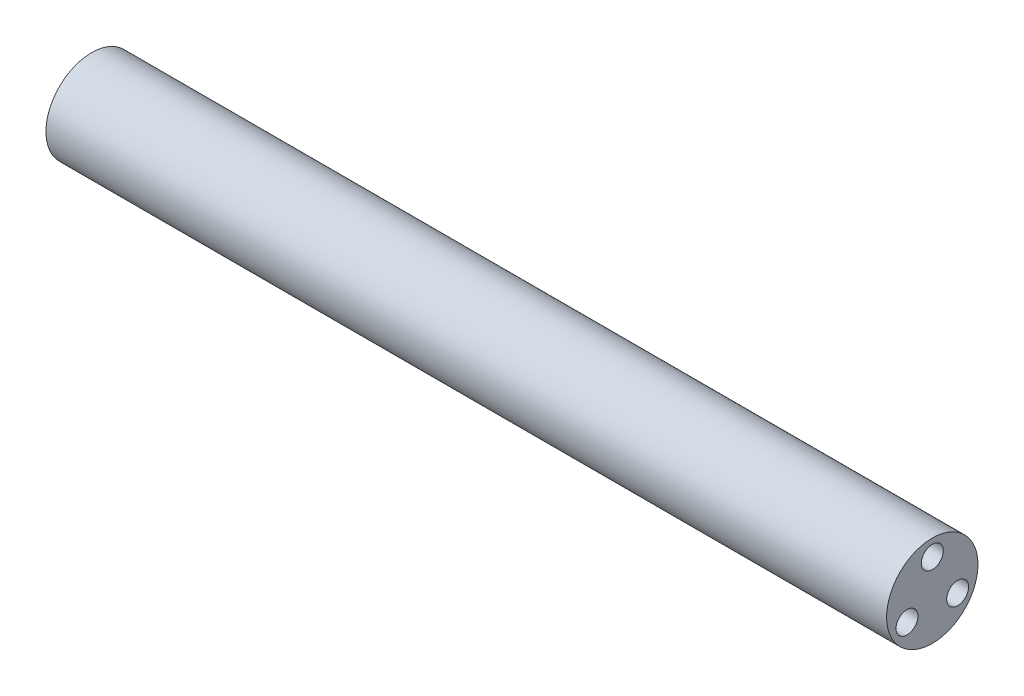
SolidWorks part; units mm, degrees
ref_plane "前视基准面" through (0, 0, 0) normal (0, 0, 1) x (1, 0, 0)
ref_plane "上视基准面" through (0, 0, 0) normal (0, 1, 0) x (1, 0, 0)
ref_plane "右视基准面" through (0, 0, 0) normal (1, 0, 0) x (0, 0, -1)
sketch "草图1" plane through (0, 0, 0) normal (1, 0, 0) x (0, 0, -1)
  circle A0 centre (0, 0) radius 12.5
extrude "凸台-拉伸1" add sketch "草图1" along normal blind 230
sketch "草图2" plane through (230, 0, 0) normal (1, 0, 0) x (0, 0, -1)
  circle A0 centre (0, 0) radius 8
  circle A1 centre (0, 8) radius 3
extrude "切除-拉伸1" cut sketch "草图2" against normal blind 20 contours A0 A1 | A0 A1
pattern_circular "阵列(圆周)1" count 3 over 360 about axis through (0, 0, 0) along (1, 0, 0) of "切除-拉伸1"
ref_plane "基准面4" through (115, 0, 0) normal (1, 0, 0) x (0, 0, -1)
mirror "镜向1" about plane through (115, 0, 0) normal (1, 0, 0) of "阵列(圆周)1", "切除-拉伸1"
sketch "草图3" plane through (230, 0, 0) normal (1, 0, 0) x (0, 0, -1)
